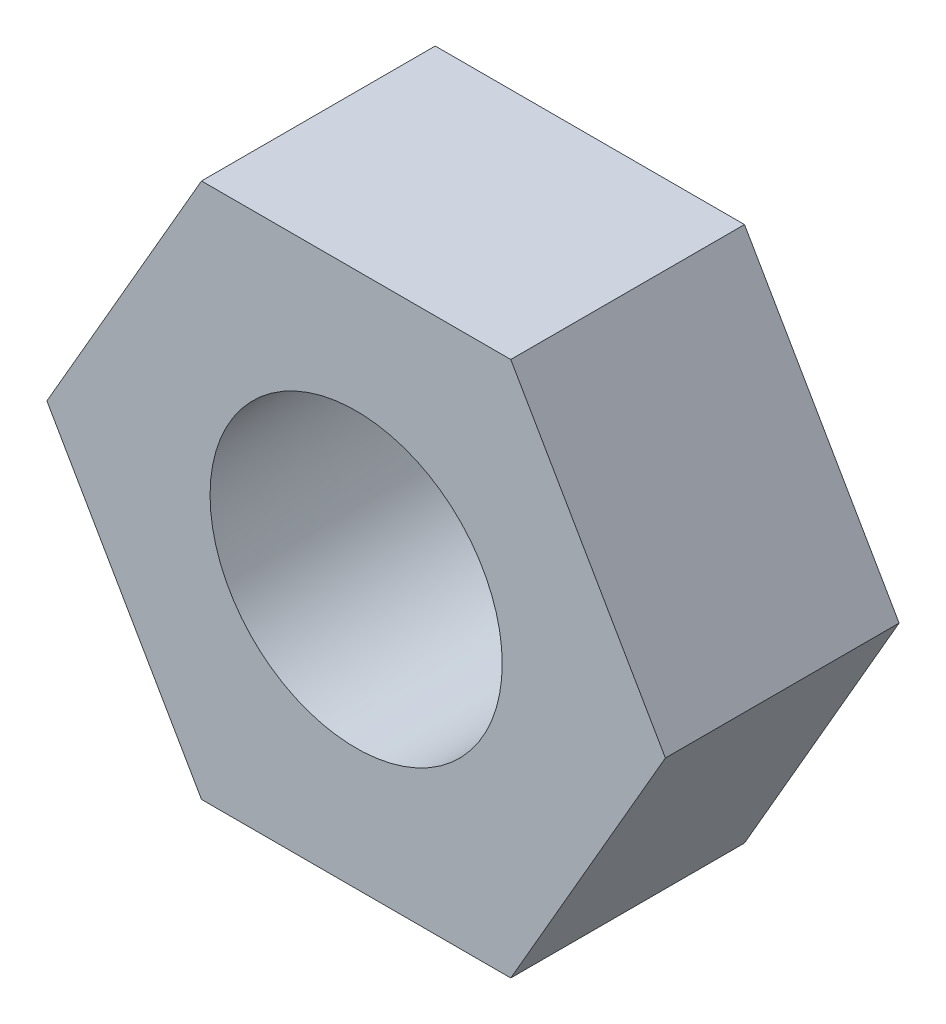
SolidWorks part; units mm, degrees
ref_plane "Front Plane" through (0, 0, 0) normal (0, 0, 1) x (1, 0, 0)
ref_plane "Top Plane" through (0, 0, 0) normal (0, 1, 0) x (1, 0, 0)
ref_plane "Right Plane" through (0, 0, 0) normal (1, 0, 0) x (0, 0, -1)
sketch "Sketch2" plane through (0, 0, 0) normal (0, 0, 1) x (1, 0, 0)
  line L1 (3.1754, 0) -> (1.5877, 2.75)
  line L2 (1.5877, 2.75) -> (-1.5877, 2.75)
  line L3 (-1.5877, 2.75) -> (-3.1754, 0)
  line L4 (-3.1754, 0) -> (-1.5877, -2.75)
  line L5 (-1.5877, -2.75) -> (1.5877, -2.75)
  line L6 (1.5877, -2.75) -> (3.1754, 0)
  circle A0 centre (0, 0) radius 2.75 construction
  dimension "D1" = 5.5
extrude "Boss-Extrude1" add sketch "Sketch2" along normal blind 2.4
sketch "Sketch3" plane through (0, 0, 0) normal (0, 0, -1) x (-1, 0, 0)
  circle A0 centre (0, 0) radius 1.5
  dimension "D1" = 3
extrude "Cut-Extrude1" cut sketch "Sketch3" against normal blind 2.4
